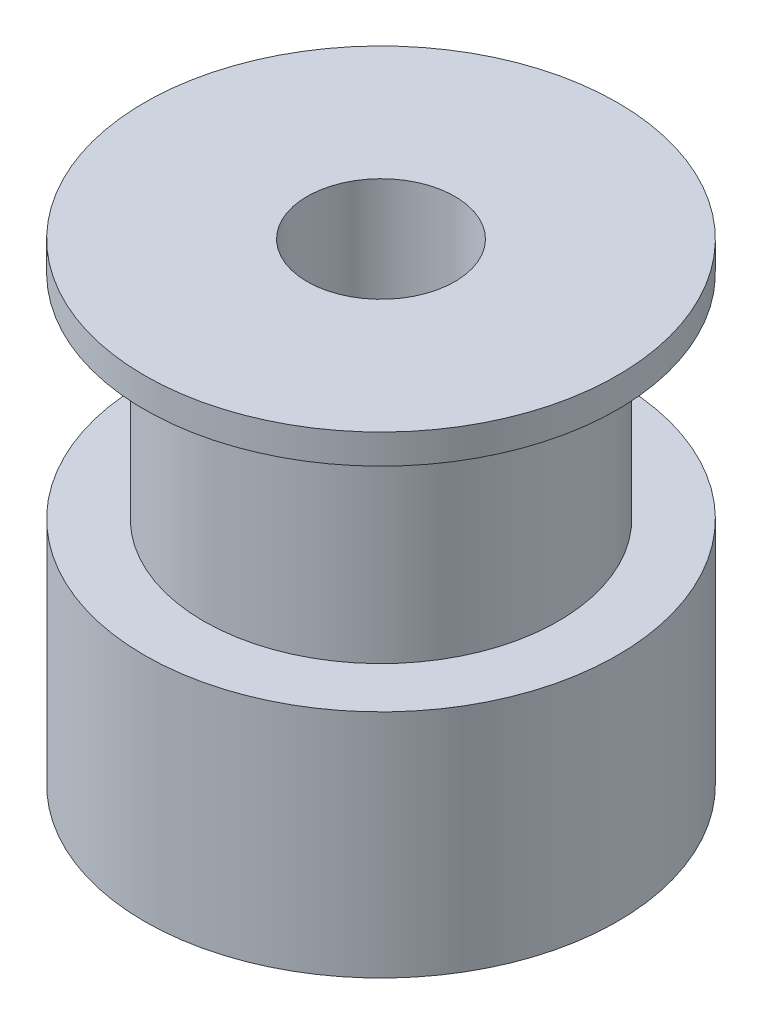
SolidWorks part; units mm, degrees
ref_plane "정면" through (0, 0, 0) normal (0, 0, 1) x (1, 0, 0)
ref_plane "윗면" through (0, 0, 0) normal (0, 1, 0) x (1, 0, 0)
ref_plane "우측면" through (0, 0, 0) normal (1, 0, 0) x (0, 0, -1)
sketch "스케치2" plane through (0, 0, 0) normal (0, 1, 0) x (1, 0, 0)
  circle A0 centre (0, 0) radius 8
  dimension "D1" = 16
extrude "보스-돌출1" add sketch "스케치2" along normal blind 16
sketch "스케치3" plane through (0, 0, 0) normal (0, 0, 1) x (1, 0, 0)
  line L0 (0, 16) -> (0, 0) construction
  line L1 (6, 15) -> (8.4353, 15)
  line L2 (6, 15) -> (6, 7.8)
  line L3 (6, 7.8) -> (8.4353, 7.8)
  line L4 (8.4353, 15) -> (8.4353, 7.8)
  line L5 (8, 16) -> (-8, 16) construction
  dimension "D1" = 6
  dimension "D2" = 1
  dimension "D3" = 7.2
revolve "컷-회전1" cut sketch "스케치3" angle 360 about axis through (0, 16, 0) along (0, -1, 0)
sketch "스케치4" plane through (0, 16, 0) normal (0, 1, 0) x (1, 0, 0)
  circle A0 centre (0, 0) radius 2.5
  dimension "D1" = 5
extrude "컷-돌출1" cut sketch "스케치4" against normal blind 16
